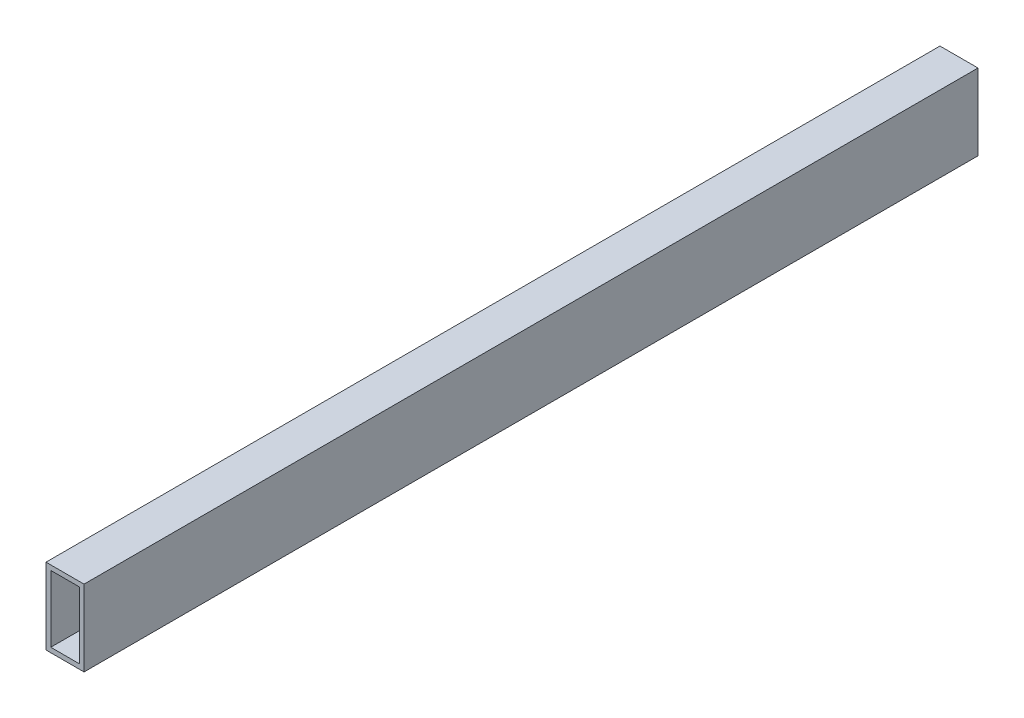
SolidWorks part; units mm, degrees
ref_plane "Front Plane" through (0, 0, 0) normal (0, 0, 1) x (1, 0, 0)
ref_plane "Top Plane" through (0, 0, 0) normal (0, 1, 0) x (1, 0, 0)
ref_plane "Right Plane" through (0, 0, 0) normal (1, 0, 0) x (0, 0, -1)
sketch "Sketch1" plane through (0, 0, 0) normal (0, 0, 1) x (1, 0, 0)
  line L0 (3.175, 47.625) -> (22.225, 47.625)
  line L1 (0, 0) -> (25.4, 0)
  line L2 (0, 0) -> (0, 50.8)
  line L3 (0, 50.8) -> (25.4, 50.8)
  line L4 (25.4, 0) -> (25.4, 50.8)
  line L5 (22.225, 3.175) -> (22.225, 47.625)
  line L6 (3.175, 3.175) -> (22.225, 3.175)
  line L7 (3.175, 3.175) -> (3.175, 47.625)
  dimension "D1" = 50.8
  dimension "D2" = 25.4
  dimension "D3" = 3.175
extrude "Boss-Extrude1" add sketch "Sketch1" along normal blind 596.9
